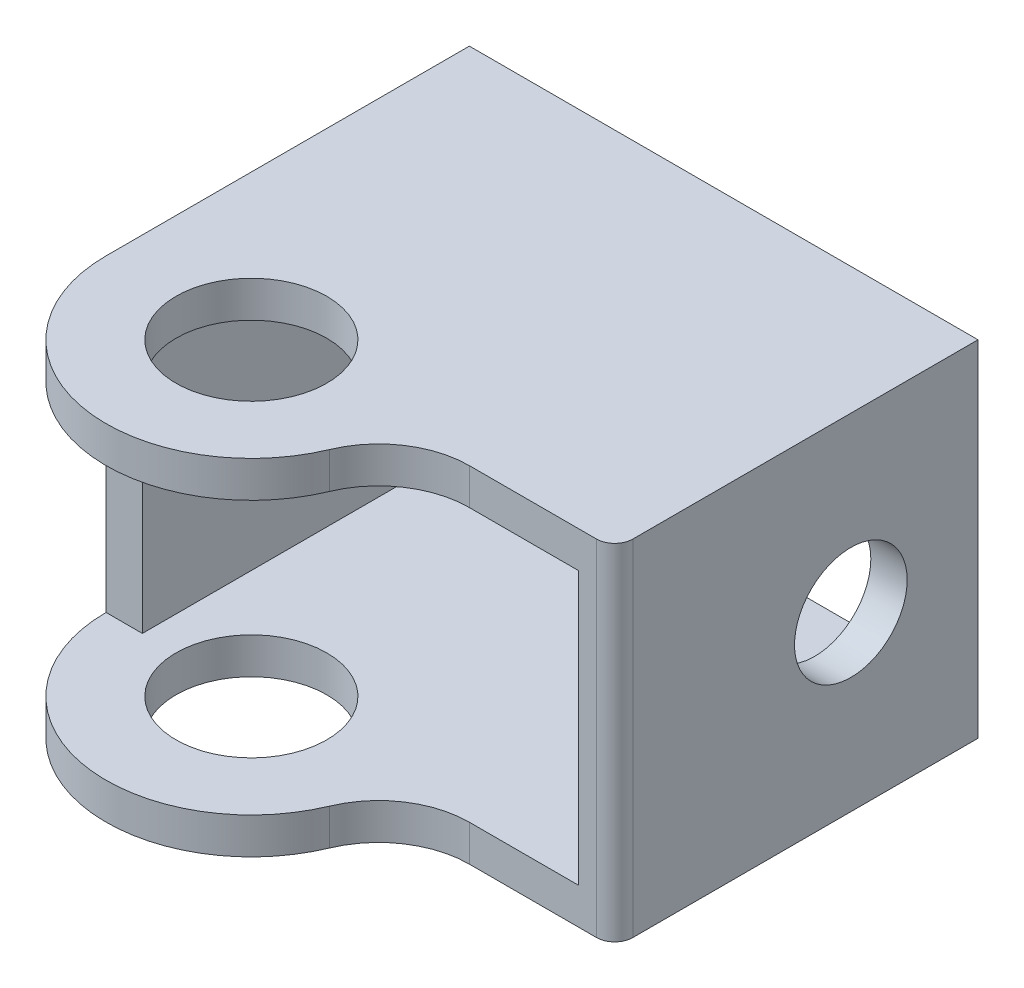
SolidWorks part; units mm, degrees
ref_plane "Front Plane" through (0, 0, 0) normal (0, 0, 1) x (1, 0, 0)
ref_plane "Top Plane" through (0, 0, 0) normal (0, 1, 0) x (1, 0, 0)
ref_plane "Right Plane" through (0, 0, 0) normal (1, 0, 0) x (0, 0, -1)
sketch "Sketch1" plane through (0, 0, 0) normal (0, 1, 0) x (1, 0, 0)
  line L1 (16.3837, 8.6283) -> (-11.6163, 8.6283)
  line L2 (16.3837, 8.6283) -> (16.3837, -10.3717)
  line L3 (15.3837, -11.3717) -> (8.3837, -11.3717)
  line L4 (-11.6163, 8.6283) -> (-11.6163, -11.3717)
  arc A0 (-7.7663, -11.3717) -> (0.5337, -11.3717) centre (-3.6163, -11.3717) ccw
  arc A1 (-11.6163, -11.3717) -> (3.7683, -14.4486) centre (-3.6163, -11.3717) ccw
  arc A2 (-7.7663, -11.3717) -> (0.5337, -11.3717) centre (-3.6163, -11.3717) cw
  arc A3 (3.7683, -14.4486) -> (8.3837, -11.3717) centre (8.3837, -16.3717) cw
  arc A4 (16.3837, -10.3717) -> (15.3837, -11.3717) centre (15.3837, -10.3717) cw
  point P12 (16.3837, -11.3717)
  dimension "D4" = 5
  dimension "D5" = 1
  dimension "D1" = 28
  dimension "D2" = 20
  dimension "D3" = 8
extrude "Boss-Extrude1" add sketch "Sketch1" along normal blind 19
sketch "Sketch2" plane through (0, 0, -8.6283) normal (0, 0, -1) x (-1, 0, 0)
  line L8 (-14.3837, 2) -> (9.6163, 2)
  line L9 (9.6163, 2) -> (9.6163, 17)
  line L10 (9.6163, 17) -> (-14.3837, 17)
  line L11 (-14.3837, 17) -> (-14.3837, 2)
  line L12 (-14.3837, 2) -> (9.6163, 2)
  line L13 (9.6163, 2) -> (9.6163, 17)
  line L14 (9.6163, 17) -> (-14.3837, 17)
  line L15 (-14.3837, 17) -> (-14.3837, 2)
  dimension "D1" = 2
extrude "Cut-Extrude1" cut sketch "Sketch2" against normal through all
sketch "Sketch3" plane through (-11.6163, 0, 0) normal (-1, 0, 0) x (0, 0, 1)
  line L0 (11.3717, 19) -> (11.3717, 0) construction
  line L1 (16.6632, 17) -> (11.3717, 17)
  line L2 (16.6632, 17) -> (16.6632, 2)
  line L3 (16.6632, 2) -> (11.3717, 2)
  line L4 (11.3717, 17) -> (11.3717, 2)
extrude "Cut-Extrude2" cut sketch "Sketch3" against normal through all
sketch "Sketch4" plane through (16.3837, 0, 0) normal (1, 0, 0) x (0, 0, -1)
  line L0 (8.6283, 9.5) -> (1.6283, 9.5)
  line L1 (8.6283, 19) -> (8.6283, 0) construction
  circle A0 centre (1.6283, 9.5) radius 3.1
  dimension "D2" = 6.2
  dimension "D1" = 7
extrude "Cut-Extrude4" cut sketch "Sketch4" against normal blind 9
